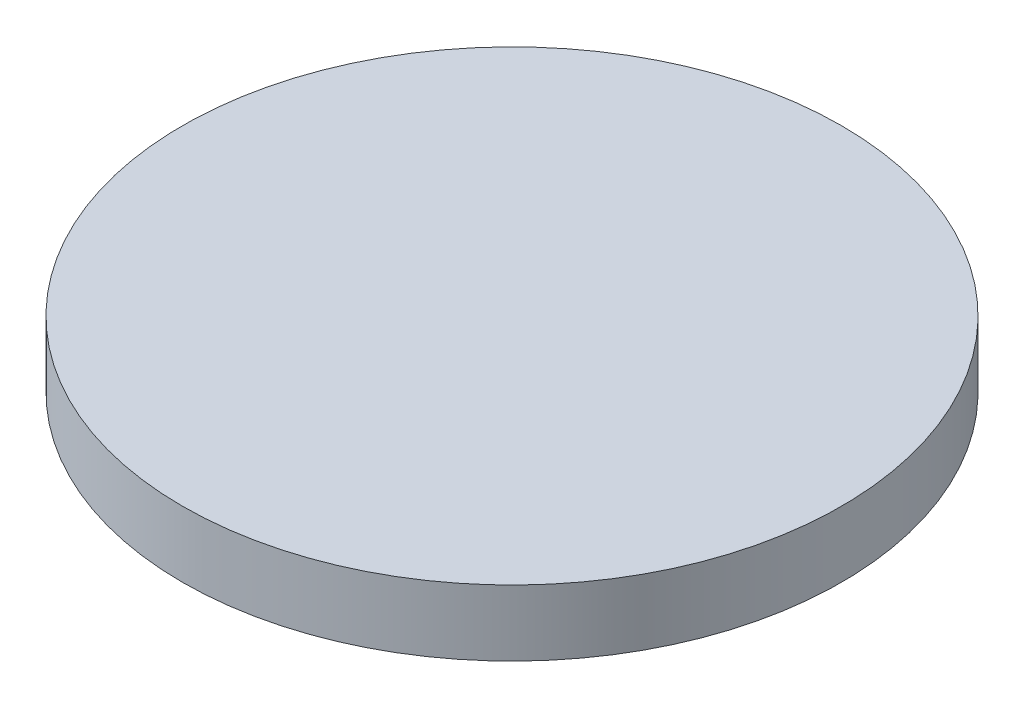
SolidWorks part; units mm, degrees
ref_plane "Front Plane" through (0, 0, 0) normal (0, 0, 1) x (1, 0, 0)
ref_plane "Top Plane" through (0, 0, 0) normal (0, 1, 0) x (1, 0, 0)
ref_plane "Right Plane" through (0, 0, 0) normal (1, 0, 0) x (0, 0, -1)
sketch "Sketch1" plane through (0, 0, 0) normal (0, 0, 1) x (1, 0, 0)
  line L0 (0, -3.175) -> (0, 3.175) construction
  line L1 (31.75, 0) -> (-31.75, 0) construction
  point P4 (0, 0)
  point P8 (0, 0)
  dimension "OD" = 63.5
  dimension "Height" = 6.35
sketch "Sketch2" plane through (0, 0, 0) normal (0, 0, 1) x (1, 0, 0)
  line L1 (0, 3.175) -> (-31.75, 3.175)
  line L2 (0, 3.175) -> (0, -3.175)
  line L3 (0, -3.175) -> (-31.75, -3.175)
  line L4 (-31.75, 3.175) -> (-31.75, -3.175)
revolve "Revolve1" add sketch "Sketch2" angle 360 about L2
